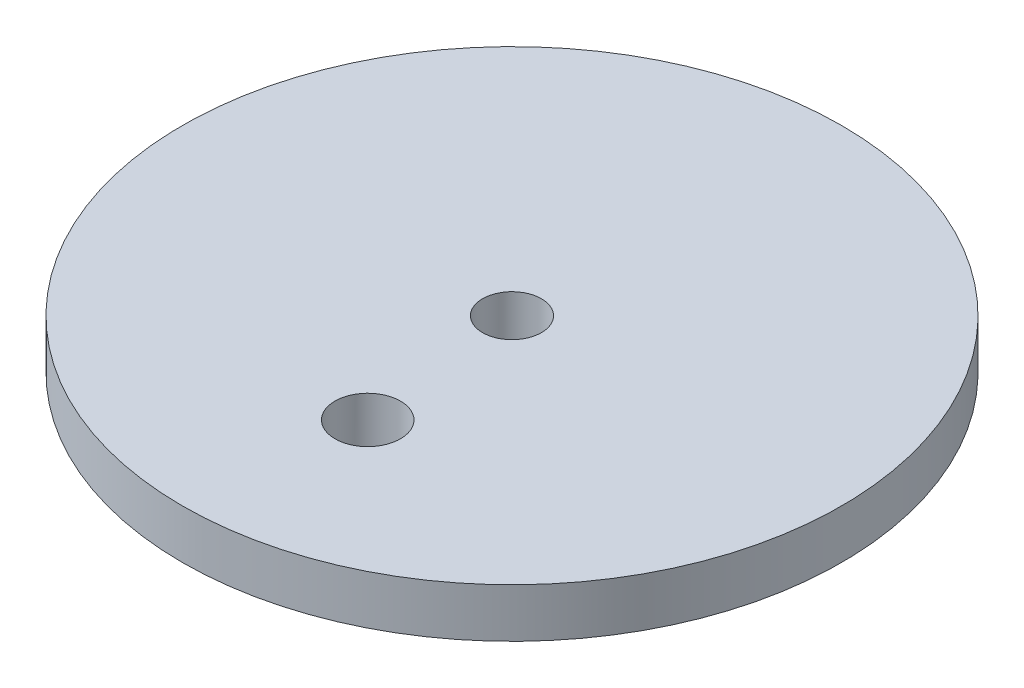
SolidWorks part; units mm, degrees
ref_plane "Front Plane" through (0, 0, 0) normal (0, 0, 1) x (1, 0, 0)
ref_plane "Top Plane" through (0, 0, 0) normal (0, 1, 0) x (1, 0, 0)
ref_plane "Right Plane" through (0, 0, 0) normal (1, 0, 0) x (0, 0, -1)
sketch "Sketch1" plane through (0, 0, 0) normal (0, 0, 1) x (1, 0, 0)
  line L0 (1.8, 9.3981) -> (1.8, 6.3981)
  line L1 (1.8, 6.3981) -> (20.1649, 6.3981)
  line L2 (20.1649, 6.3981) -> (20.1649, 9.3981)
  line L3 (20.1649, 9.3981) -> (1.8, 9.3981)
  line L4 (0, 9.3981) -> (0, 6.3981) construction
revolve "Revolve1" add sketch "Sketch1" angle 360 about L4
sketch "Sketch2" plane through (0, 9.3981, 0) normal (0, 1, 0) x (1, 0, 0)
  circle A0 centre (1.1099, -9.9382) radius 2.0031
  circle A1 centre (0, 0) radius 1.8 construction
  dimension "D1" = 10
extrude "Cut-Extrude1" cut sketch "Sketch2" against normal blind 10
